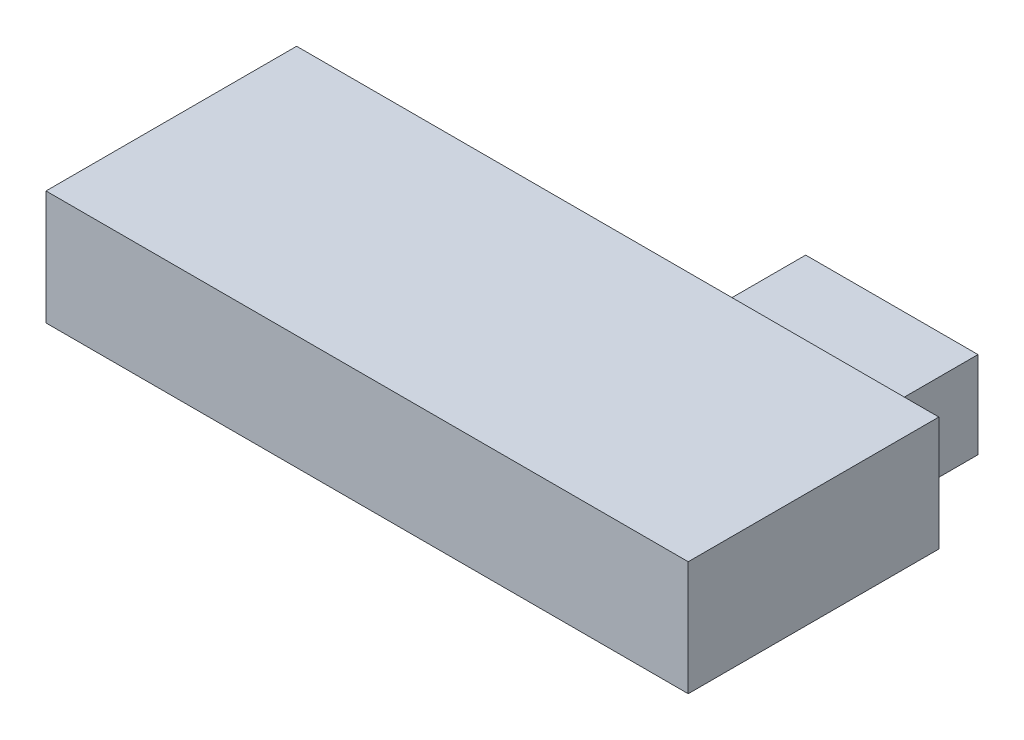
SolidWorks part; units mm, degrees
material "尼龙 101"
ref_plane "前视基准面" through (0, 0, 0) normal (0, 0, 1) x (1, 0, 0)
ref_plane "上视基准面" through (0, 0, 0) normal (0, 1, 0) x (1, 0, 0)
ref_plane "右视基准面" through (0, 0, 0) normal (1, 0, 0) x (0, 0, -1)
sketch "草图1" plane through (0, 0, 0) normal (0, 1, 0) x (1, 0, 0)
  line L1 (0, 0) -> (41, 0)
  line L2 (0, 0) -> (0, 16)
  line L3 (0, 16) -> (41, 16)
  line L4 (41, 0) -> (41, 16)
  dimension "D1" = 41
  dimension "D2" = 16
extrude "凸台-拉伸1" add sketch "草图1" along normal blind 7.3
sketch "草图2" plane through (0, 0, -16) normal (0, 0, -1) x (-1, 0, 0)
  line L0 (-38, -4.0246) -> (-38, 10.7749) construction
  line L1 (-27, -5.4199) -> (-27, 10.3097) construction
  line L2 (-41, 7.3) -> (-41, 0) construction
  line L4 (-27, 6.5042) -> (-38, 6.5042)
  line L5 (-27, 6.5042) -> (-27, 0.965)
  line L6 (-27, 0.965) -> (-38, 0.965)
  line L7 (-38, 6.5042) -> (-38, 0.965)
  dimension "D1" = 3
  dimension "D2" = 11
extrude "凸台-拉伸2" add sketch "草图2" along normal blind 5.5
